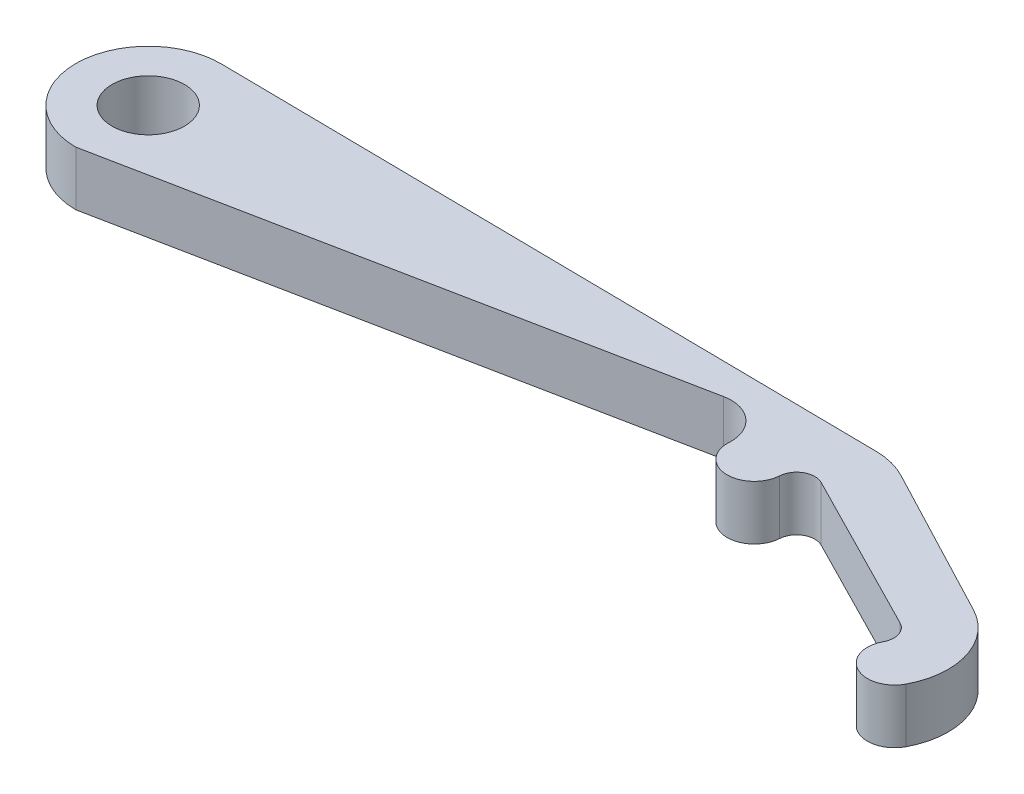
SolidWorks part; units mm, degrees
material "AISI 1045 Steel, cold drawn"
ref_plane "Front Plane" through (0, 0, 0) normal (1, 0, 0) x (0, 1, 0)
ref_plane "Top Plane" through (0, 0, 0) normal (0, 0, 1) x (0, 1, 0)
ref_plane "Right Plane" through (0, 0, 0) normal (0, 1, 0) x (-1, 0, 0)
sketch "Sketch1" plane through (0, 0, 0) normal (0, 1, 0) x (-1, 0, 0)
  line L0 (-42.629, 0) -> (46.0829, 0) construction
  line L1 (0, 11.7425) -> (0, -12.3386) construction
  line L2 (23.645, -4.0003) -> (-13.024, -3.5515)
  line L3 (23.645, 4) -> (-6.1796, -1.9589)
  line L4 (42.6361, -0.03) -> (-6.565, -0.03) construction
  line L5 (-12.525, 0.35) -> (46.0829, 0.35) construction
  line L6 (-21.8897, 3.9987) -> (-12.9817, -0.5454)
  line L7 (-14.8342, -3.0934) -> (-23.2945, 1.3478)
  arc A0 (-22.3193, 5.3582) -> (-24.9707, 6.7618) centre (-23.645, 6.06) ccw
  circle A1 centre (23.645, 0) radius 2
  circle A2 centre (23.645, 0) radius 4
  arc A3 (-8.4949, 0.35) -> (-6.1796, -1.9589) centre (-6.565, -0.03) ccw
  arc A4 (-8.5371, 0) -> (-11.5129, 0) centre (-10.025, 0.19) ccw
  arc A5 (-22.3193, 5.3582) -> (-21.8897, 3.9987) centre (-21.435, 4.89) ccw
  arc A6 (-12.9817, -0.5454) -> (-11.5199, 0.35) centre (-12.525, 0.35) ccw
  arc A7 (-13.024, -3.5515) -> (-14.8342, -3.0934) centre (-12.975, 0.4482) cw
  arc A8 (-24.9707, 6.7618) -> (-23.2945, 1.3478) centre (-21.435, 4.89) ccw
  dimension "D2" = 3
  dimension "D3" = 8
  dimension "D4" = 4
  dimension "D10" = 3
  dimension "D11" = 33.67
  dimension "D12" = 45.08
  dimension "D13" = 4.89
  dimension "D14" = 36.62
  dimension "D15" = 36.17
  dimension "D21" = 4
  dimension "D1" = 6.06
  dimension "D5" = 47.29
  dimension "D6" = 23.645
  dimension "D7" = 12
  dimension "D9" = 30.21
  dimension "D17" = 0.03
  dimension "D18" = 0.35
  dimension "D19" = 0.19
extrude "Boss-Extrude1" add sketch "Sketch1" along normal blind 3
